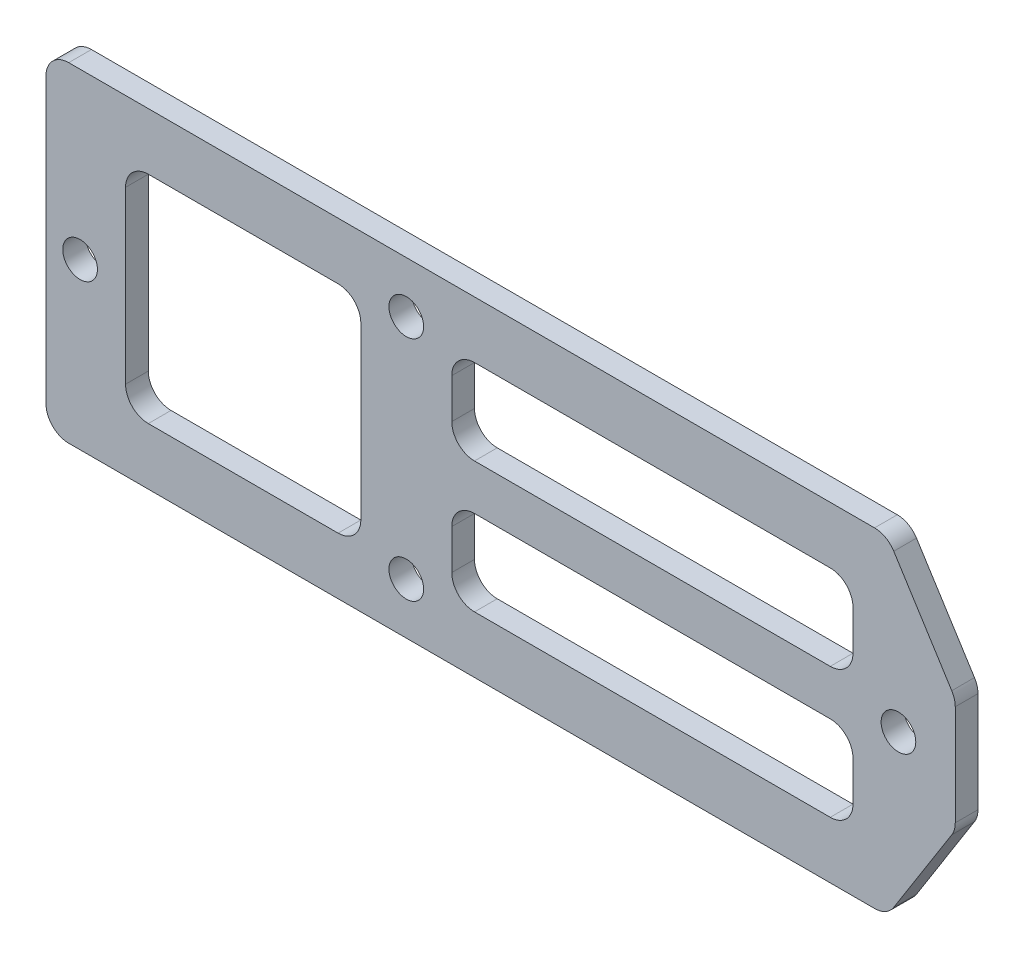
SolidWorks part; units mm, degrees
material "Thornel Mat VMA"
ref_plane "前视基准面" through (0, 0, 0) normal (0, 0, 1) x (1, 0, 0)
ref_plane "上视基准面" through (0, 0, 0) normal (0, 1, 0) x (1, 0, 0)
ref_plane "右视基准面" through (0, 0, 0) normal (1, 0, 0) x (0, 0, -1)
other "Configuration Table"
sketch "草图1" plane through (0, 0, 0) normal (0, 0, 1) x (1, 0, 0)
  line L1 (-40, -14.5) -> (40, -14.5)
  line L2 (-40, -14.5) -> (-40, 14.5)
  line L3 (-40, 14.5) -> (40, 14.5)
  line L4 (40, -14.5) -> (40, 14.5)
  line L5 (-40, -14.5) -> (40, 14.5) construction
  line L6 (-40, 14.5) -> (40, -14.5) construction
  point P0 (0, 0)
  dimension "D1" = 29
  dimension "D2" = 80
extrude "凸台-拉伸1" add sketch "草图1" along normal blind 2
sketch "草图2" plane through (0, 0, 2) normal (0, 0, 1) x (1, 0, 0)
  line L0 (34, 14.5) -> (40, 5)
  line L1 (40, 14.5) -> (-40, 14.5) construction
  line L2 (40, -14.5) -> (40, 14.5) construction
  line L3 (40, 5) -> (40, 14.5)
  line L4 (40, 14.5) -> (34, 14.5)
  line L5 (0, 0) -> (40, 0) construction
  line L6 (40, -14.5) -> (34, -14.5)
  line L7 (40, -5) -> (40, -14.5)
  line L8 (34, -14.5) -> (40, -5)
  dimension "D1" = 5
  dimension "D2" = 6
extrude "切除-拉伸1" cut sketch "草图2" against normal blind 2
sketch "草图3" plane through (0, 0, 2) normal (0, 0, 1) x (1, 0, 0)
  circle A0 centre (-37, 0) radius 1.7 construction
  circle A1 centre (-8.3, -10) radius 1.7 construction
  circle A2 centre (-8.3, 10) radius 1.7 construction
  circle A3 centre (-37, 0) radius 1.7 construction
  circle A4 centre (-8.3, -10) radius 1.7 construction
  circle A5 centre (-8.3, 10) radius 1.7 construction
  circle A6 centre (-8.3, 10) radius 1.525
  circle A7 centre (-37, 0) radius 1.525
  circle A8 centre (-8.3, -10) radius 1.525
  dimension "D1" = 3.05
extrude "切除-拉伸2" cut sketch "草图3" against normal blind 10
sketch "草图4" plane through (0, 0, 2) normal (0, 0, 1) x (1, 0, 0)
  circle A0 centre (35, 0) radius 1.25 construction
  circle A1 centre (35, 0) radius 1.25 construction
  circle A2 centre (35, 0) radius 1.525
  dimension "D1" = 3.05
extrude "切除-拉伸3" cut sketch "草图4" against normal blind 10
fillet "圆角1" radius 2 6 edges at (40, -5, 1) (34, -14.5, 1) (34, 14.5, 1) (40, 5, 1) (-40, 14.5, 1) (-40, -14.5, 1)
sketch "草图5" plane through (0, 0, 2) normal (0, 0, 1) x (1, 0, 0)
  line L0 (-33, 9.5) -> (-33, -9.5)
  line L1 (-33, -9.5) -> (-12.3, -9.5)
  line L2 (-12.3, -9.5) -> (-12.3, 9.5)
  line L3 (-12.3, 9.5) -> (-33, 9.5)
  line L4 (32.8977, 14.5) -> (-38, 14.5) construction
  line L5 (-33, 0) -> (0, 0) construction
  circle A0 centre (-37, 0) radius 1.525 construction
  circle A1 centre (-8.3, 10) radius 1.525 construction
  dimension "D1" = 4
  dimension "D2" = 5
  dimension "D3" = 4
extrude "切除-拉伸4" cut sketch "草图5" against normal blind 10
sketch "草图6" plane through (0, 0, 2) normal (0, 0, 1) x (1, 0, 0)
  line L0 (-12.3, 9.5) -> (-33, 9.5) construction
  line L1 (-4.3, -9.5) -> (31, -9.5)
  line L2 (-4.3, -9.5) -> (-4.3, 9.5)
  line L3 (-4.3, 9.5) -> (31, 9.5)
  line L4 (31, -9.5) -> (31, 9.5)
  line L5 (-33, -9.5) -> (-12.3, -9.5) construction
  line L6 (-4.3, 0) -> (31, 0) construction
  line L7 (-4.3, -2) -> (31, -2)
  line L8 (-4.3, 2) -> (31, 2)
  circle A0 centre (35, 0) radius 1.525 construction
  circle A1 centre (-8.3, 10) radius 1.525 construction
  dimension "D1" = 4
  dimension "D2" = 4
  dimension "D3" = 2
  dimension "D4" = 2
extrude "切除-拉伸5" cut sketch "草图6" against normal blind 10 contours L2 L8 L4 L3 | L7 L2 L1 L4
fillet "圆角2" radius 2 12 edges at (31, 9.5, 1) (31, 2, 1) (31, -9.5, 1) (-4.3, -9.5, 1) (-4.3, -2, 1) (31, -2, 1) (-12.3, 9.5, 1) (-12.3, -9.5, 1) (-33, -9.5, 1) (-33, 9.5, 1) (-4.3, 9.5, 1) (-4.3, 2, 1)
